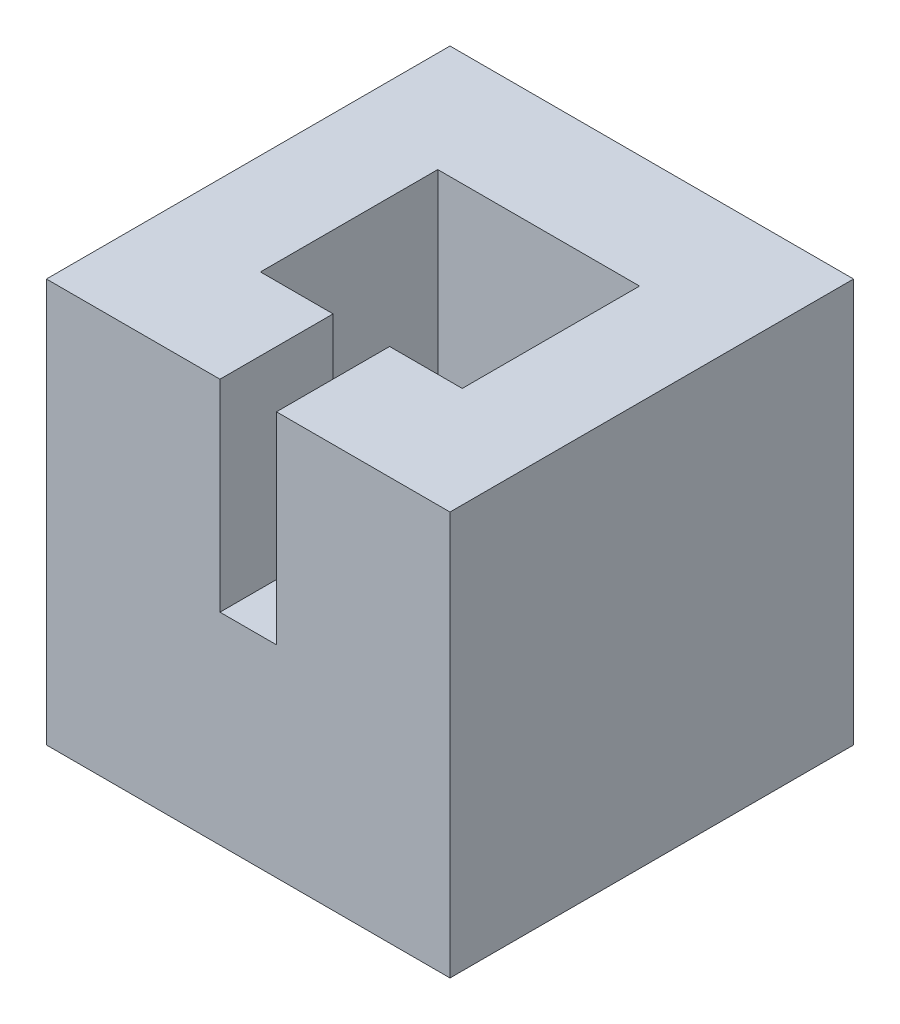
SolidWorks part; units mm, degrees
ref_plane "Front Plane" through (0, 0, 0) normal (0, 0, 1) x (1, 0, 0)
ref_plane "Top Plane" through (0, 0, 0) normal (0, 1, 0) x (1, 0, 0)
ref_plane "Right Plane" through (0, 0, 0) normal (1, 0, 0) x (0, 0, -1)
sketch "Sketch1" plane through (0, 0, 0) normal (0, 1, 0) x (1, 0, 0)
  line L1 (-6.35, -6.35) -> (6.35, -6.35)
  line L2 (-6.35, -6.35) -> (-6.35, 6.35)
  line L3 (-6.35, 6.35) -> (6.35, 6.35)
  line L4 (6.35, -6.35) -> (6.35, 6.35)
  line L5 (-6.35, -6.35) -> (6.35, 6.35) construction
  line L6 (-6.35, 6.35) -> (6.35, -6.35) construction
  point P0 (0, 0)
  dimension "D1" = 12.7
  dimension "D2" = 12.7
extrude "Boss-Extrude1" add sketch "Sketch1" along normal blind 12.7
sketch "Sketch2" plane through (0, 12.7, 0) normal (0, 1, 0) x (1, 0, 0)
  line L0 (-6.35, -6.35) -> (6.35, -6.35) construction
  line L1 (-0.889, -9.91) -> (0.889, -9.91)
  line L2 (-0.889, -9.91) -> (-0.889, -2.79)
  line L3 (-0.889, -2.79) -> (0.889, -2.79)
  line L4 (0.889, -9.91) -> (0.889, -2.79)
  line L5 (-0.889, -9.91) -> (0.889, -2.79) construction
  line L6 (-0.889, -2.79) -> (0.889, -9.91) construction
  line L8 (-3.175, 2.79) -> (3.175, 2.79)
  line L9 (-3.175, 2.79) -> (-3.175, -2.79)
  line L10 (-3.175, -2.79) -> (3.175, -2.79)
  line L11 (3.175, 2.79) -> (3.175, -2.79)
  line L12 (-3.175, 2.79) -> (3.175, -2.79) construction
  line L13 (-3.175, -2.79) -> (3.175, 2.79) construction
  point P0 (0, -6.35)
  point P7 (0, 0)
  line M6 (-6.35, -6.35) -> (6.35, -6.35)
  dimension "D1" = 1.778
  dimension "D2" = 6.35
extrude "Cut-Extrude1" cut sketch "Sketch2" against normal blind 6.35 contours L11 L8 L9 L10 L3 | L4 L3 L2 M6
